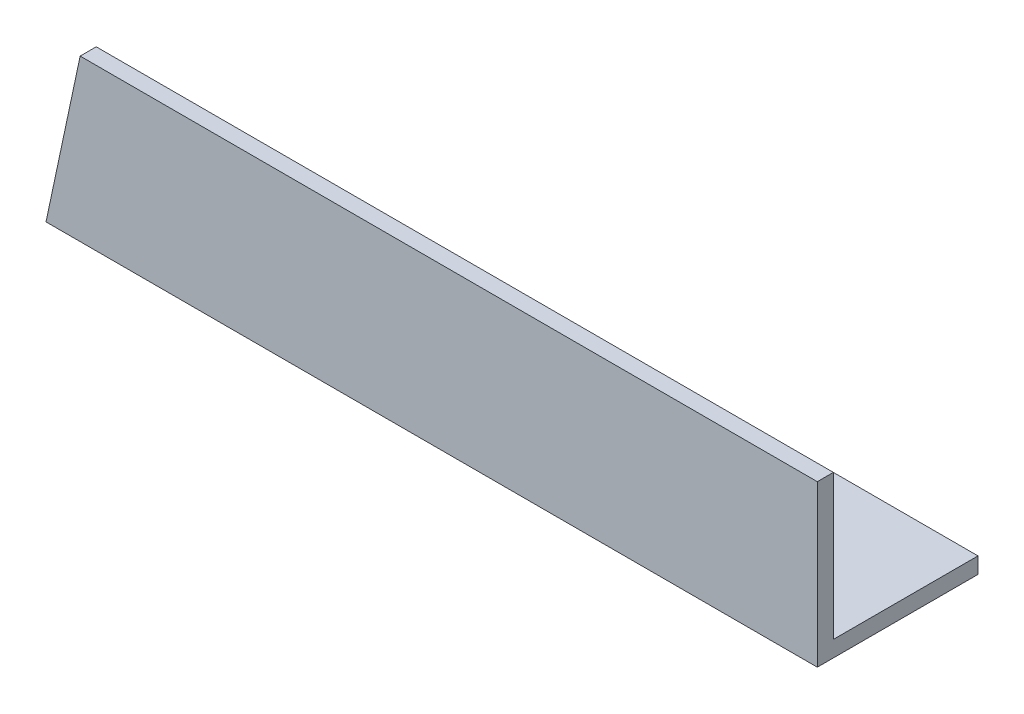
SolidWorks part; units mm, degrees
ref_plane "Front Plane" through (0, 0, 0) normal (0, 0, 1) x (1, 0, 0)
ref_plane "Top Plane" through (0, 0, 0) normal (0, 1, 0) x (1, 0, 0)
ref_plane "Right Plane" through (0, 0, 0) normal (1, 0, 0) x (0, 0, -1)
sketch "Sketch1" plane through (0, 0, 0) normal (1, 0, 0) x (0, 0, -1)
  line L0 (0, 20) -> (0, 0)
  line L1 (0, 0) -> (20, 0)
  line L2 (20, 0) -> (20, 2)
  line L3 (20, 2) -> (2, 2)
  line L4 (2, 2) -> (2, 20)
  line L5 (0, 20) -> (2, 20)
  dimension "D1" = 20
  dimension "D2" = 20
  dimension "D3" = 2
  dimension "D4" = 2
extrude "Boss-Extrude1" add sketch "Sketch1" along normal blind 96
sketch "Sketch2" plane through (0, 0, 0) normal (0, 0, 1) x (1, 0, 0)
  line L0 (0, 0) -> (4.2511, 20)
  line L1 (96, 20) -> (0, 20) construction
  line L2 (4.2511, 20) -> (0, 20)
  line L3 (0, 20) -> (0, 0)
  dimension "D1" = 12
extrude "Cut-Extrude1" cut sketch "Sketch2" against normal through all
